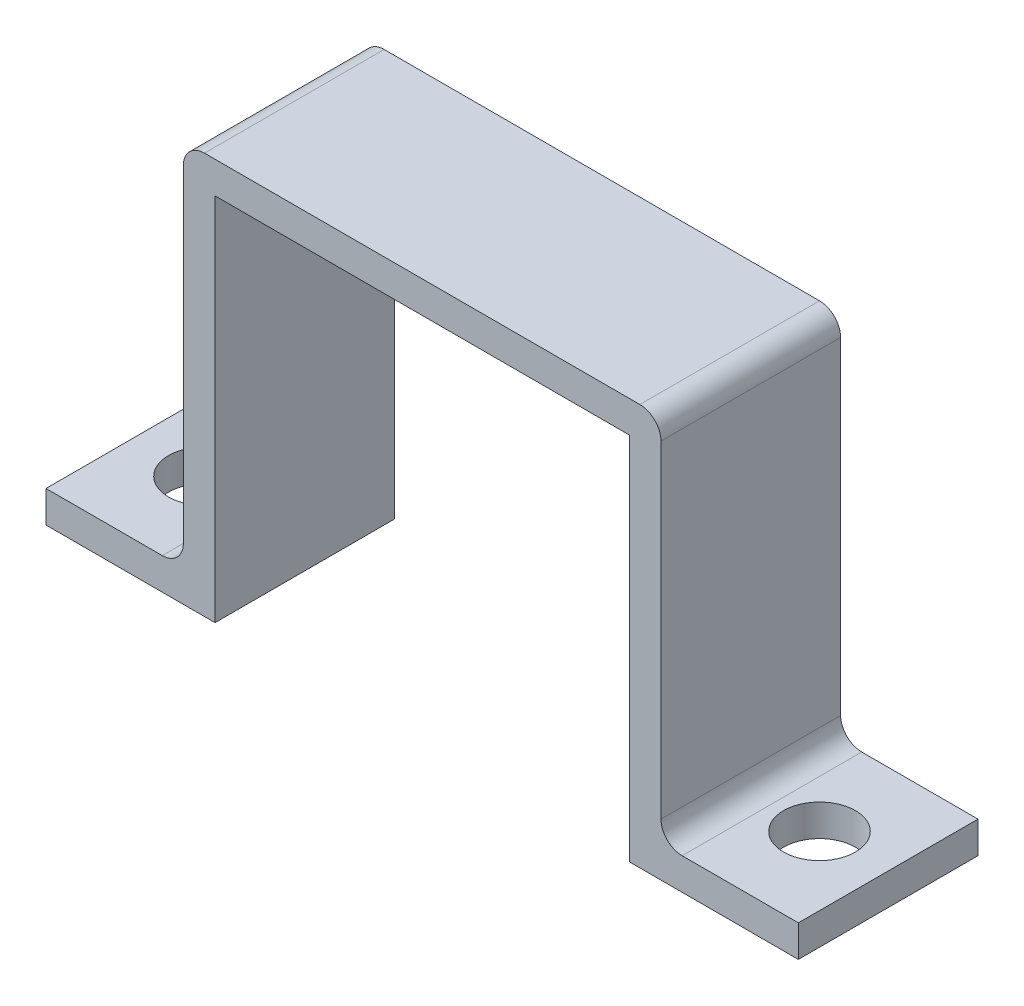
SolidWorks part; units mm, degrees
ref_plane "Front" through (0, 0, 0) normal (0, 0, 1) x (1, 0, 0)
ref_plane "Top" through (0, 0, 0) normal (0, 1, 0) x (1, 0, 0)
ref_plane "Right" through (0, 0, 0) normal (1, 0, 0) x (0, 0, -1)
sketch "Sketch1" plane through (0, 0, 0) normal (0, 0, 1) x (1, 0, 0)
  line L0 (-17.8, 0) -> (-17.8, 1.5)
  line L3 (-9.8, 17.49) -> (9.8, 17.49)
  line L4 (9.8, 0) -> (9.8, 17.49)
  line L5 (0, 18.99) -> (0, 0) construction
  line L6 (-11.3, 18.99) -> (11.3, 18.99)
  line L11 (-11.3, 1.5) -> (-17.8, 1.5)
  line L12 (-9.8, 0) -> (-17.8, 0)
  line L13 (-11.3, 1.5) -> (-11.3, 18.99)
  line L19 (11.3, 1.5) -> (11.3, 18.99)
  line L20 (9.8, 0) -> (17.8, 0)
  line L22 (11.3, 1.5) -> (17.8, 1.5)
  line L23 (17.8, 0) -> (17.8, 1.5)
  line L24 (-9.8, 0) -> (-9.8, 17.49)
  point P0 (0, 0)
  point P14 (0, 17.49)
  dimension "D1" = 9.8
  dimension "D3" = 1.5
  dimension "D4" = 1.5
  dimension "D5" = 1.5
  dimension "D6" = 8
  dimension "D2" = 17.49
extrude "Boss-Extrude1" add sketch "Sketch1" along normal blind 8.5
sketch "Sketch2" plane through (0, 1.5, 0) normal (0, 1, 0) x (1, 0, 0)
  line L0 (11.3, -8.5) -> (11.3, 0) construction
  line L2 (17.8, 0) -> (11.3, 0) construction
  circle A0 centre (14.55, -4.25) radius 1.7
  point P5 (11.3, -4.25)
  point P7 (14.55, 0)
  dimension "D1" = 3.4
extrude "Cut-Extrude1" cut sketch "Sketch2" against normal through all
fillet "Fillet1" radius 1 4 edges at (11.3, 1.5, 4.25) (11.3, 18.99, 4.25) (-11.3, 18.99, 4.25) (-11.3, 1.5, 4.25)
mirror "Mirror1" about plane through (0, 0, 0) normal (1, 0, 0) of "Cut-Extrude1"
equation "\"Jack Height\"= 17.49"
equation "\"Jack Width\"= 19.6"
equation "\"Wall Thickness\"= 1.5"
equation "\"Mount Length\"= 8.5"
equation "\"D1@Boss-Extrude1\"=\"Mount Length\""
equation "\"D1@Sketch1\"=\"Jack Width\"/2"
equation "\"D3@Sketch1\"=\"Wall Thickness\""
equation "\"D4@Sketch1\"=\"Wall Thickness\""
equation "\"D2@Sketch1\"=\"Jack Height\""
